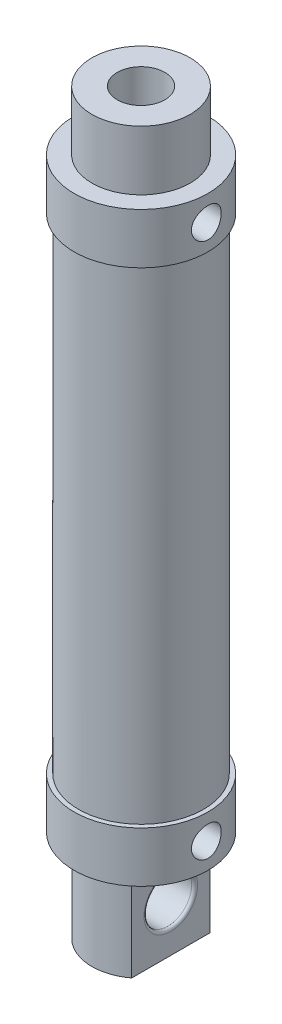
SolidWorks part; units mm, degrees
ref_plane "前视基准面" through (0, 0, 0) normal (0, 0, 1) x (1, 0, 0)
ref_plane "上视基准面" through (0, 0, 0) normal (0, 1, 0) x (1, 0, 0)
ref_plane "右视基准面" through (0, 0, 0) normal (1, 0, 0) x (0, 0, -1)
sketch "草图1" plane through (0, 0, 0) normal (0, 1, 0) x (1, 0, 0)
  circle A0 centre (0, 0) radius 21
  circle A1 centre (0, 0) radius 17.5
  dimension "D1" = 42
  dimension "D2" = 35
extrude "拉伸1" add sketch "草图1" along normal blind 163
sketch "草图2" plane through (0, 0, 0) normal (0, -1, 0) x (1, 0, 0)
  circle A0 centre (0, 0) radius 22.5
  dimension "D1" = 45
extrude "拉伸2" add sketch "草图2" along normal blind 17
ref_plane "基准面1" through (22.5, 0, 0) normal (1, 0, 0) x (0, 0, -1)
sketch "草图4" plane through (22.5, 0, 0) normal (1, 0, 0) x (0, 0, -1)
  line L0 (-22.5, -17) -> (22.5, -17) construction
  circle A0 centre (0, -8.5) radius 5
  dimension "D1" = 10
  dimension "D2" = 8.5
extrude "拉伸3" cut sketch "草图4" against normal blind 17
ref_plane "基准面2" through (0, 81.5, 0) normal (0, 1, 0) x (-1, 0, 0)
mirror "镜向1" about plane through (0, 81.5, 0) normal (0, 1, 0) of "拉伸2", "拉伸3"
sketch "草图5" plane through (0, -17, 0) normal (0, -1, 0) x (1, 0, 0)
  line L2 (10, -13.1244) -> (10, 13.1244)
  line L4 (-10, -13.1244) -> (-10, 13.1244)
  line L5 (10, -20.1556) -> (-10, 20.1556) construction
  line L6 (10, 20.1556) -> (-10, -20.1556) construction
  circle A0 centre (0, 0) radius 22.5 construction
  arc A1 (-10, -13.1244) -> (10, -13.1244) centre (0, 0) ccw
  arc A2 (10, 13.1244) -> (-10, 13.1244) centre (0, 0) ccw
  point P0 (0, 0)
  dimension "D2" = 33
  dimension "D1" = 20
extrude "拉伸4" add sketch "草图5" along normal blind 31
sketch "草图6" plane through (10, 0, 0) normal (1, 0, 0) x (0, 0, -1)
  line L0 (13.1244, -17) -> (-13.1244, -17) construction
  circle A0 centre (0, -32) radius 8
  dimension "D1" = 16
  dimension "D2" = 15
extrude "拉伸5" cut sketch "草图6" against normal blind 31
fillet "圆角1" radius 1 2 edges at (-10, -32, -8) (10, -32, -8)
sketch "草图7" plane through (0, 180, 0) normal (0, 1, 0) x (1, 0, 0)
  circle A0 centre (0, 0) radius 16.5
  dimension "D1" = 33
extrude "拉伸6" add sketch "草图7" along normal blind 20
sketch "草图8" plane through (0, 200, 0) normal (0, 1, 0) x (1, 0, 0)
  circle A0 centre (0, 0) radius 8
  dimension "D1" = 16
extrude "拉伸9" cut sketch "草图8" against normal up to next
